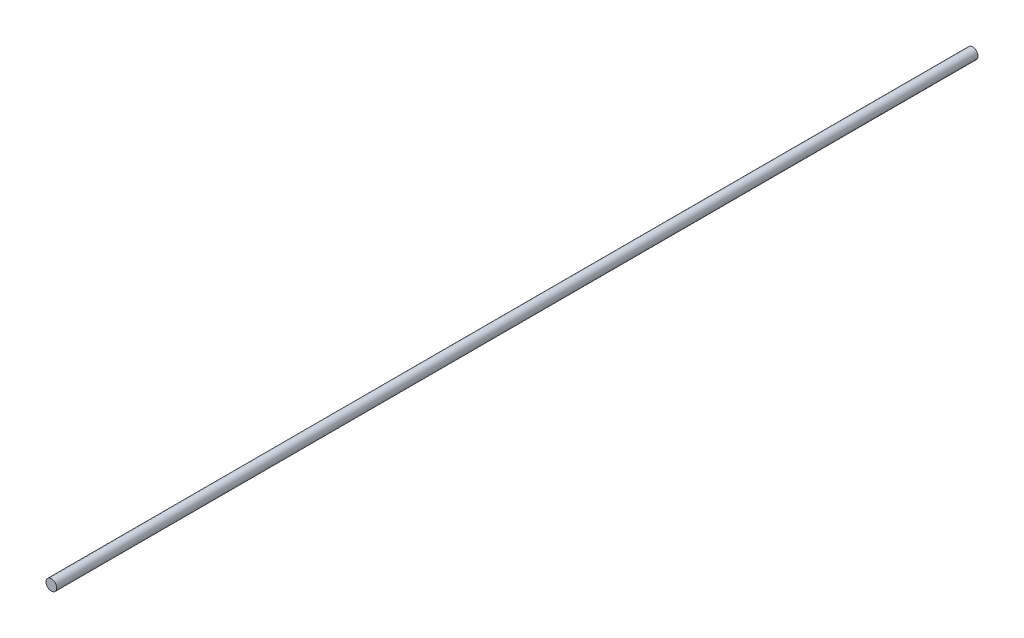
SolidWorks part; units mm, degrees
ref_plane "Plan de face" through (0, 0, 0) normal (0, 0, 1) x (1, 0, 0)
ref_plane "Plan de dessus" through (0, 0, 0) normal (0, 1, 0) x (1, 0, 0)
ref_plane "Plan de droite" through (0, 0, 0) normal (1, 0, 0) x (0, 0, -1)
sketch "Esquisse1" plane through (0, 0, 0) normal (0, 0, 1) x (1, 0, 0)
  circle A1 centre (0, 1) radius 0.5
extrude "Boss.-Extru.1" add sketch "Esquisse1" against normal blind 83 and the other way blind 3
